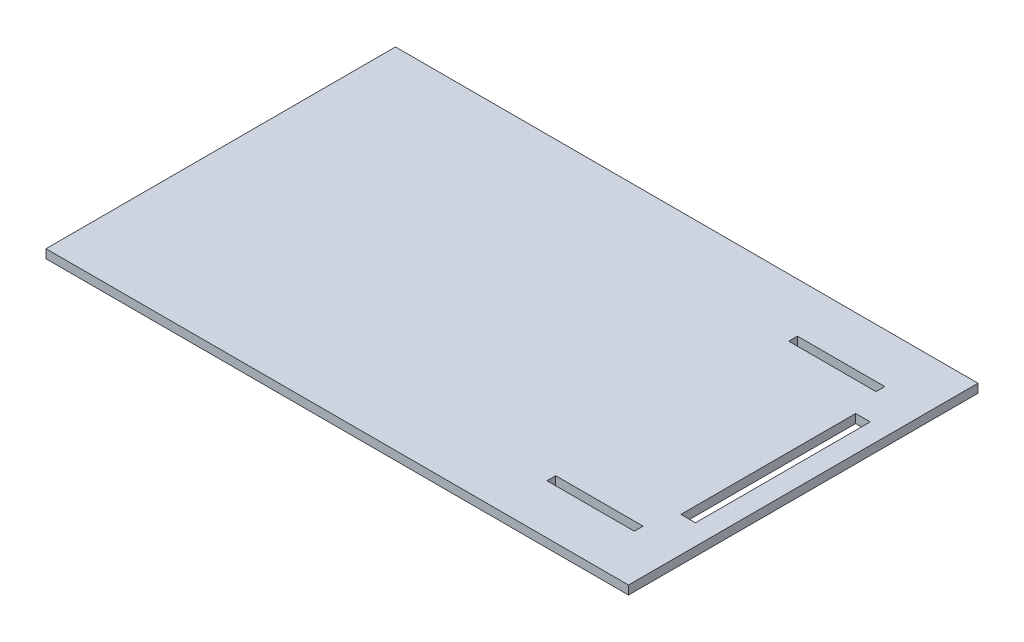
SolidWorks part; units mm, degrees
ref_plane "Front Plane" through (0, 0, 0) normal (0, 0, 1) x (1, 0, 0)
ref_plane "Top Plane" through (0, 0, 0) normal (0, 1, 0) x (1, 0, 0)
ref_plane "Right Plane" through (0, 0, 0) normal (1, 0, 0) x (0, 0, -1)
sketch "Sketch1" plane through (0, 0, 0) normal (0, 1, 0) x (1, 0, 0)
  line L1 (100, -60) -> (-100, -60)
  line L2 (100, -60) -> (100, 60)
  line L3 (100, 60) -> (-100, 60)
  line L4 (-100, -60) -> (-100, 60)
  line L5 (100, -60) -> (-100, 60) construction
  line L6 (100, 60) -> (-100, -60) construction
  point P0 (0, 0)
  dimension "D1" = 200
  dimension "D2" = 120
extrude "Boss-Extrude1" add sketch "Sketch1" along normal blind 3
sketch "Sketch2" plane through (0, 3, 0) normal (0, 1, 0) x (1, 0, 0)
  line L0 (0, 0) -> (100, 0) construction
  line L1 (88, 30) -> (93, 30)
  line L2 (88, 30) -> (88, -30)
  line L3 (88, -30) -> (93, -30)
  line L4 (93, 30) -> (93, -30)
  line L5 (88, 30) -> (93, -30) construction
  line L6 (88, -30) -> (93, 30) construction
  line L7 (100, -60) -> (100, 60) construction
  line L8 (100, 0) -> (0, 0) construction
  line L9 (0, 0) -> (0, 60) construction
  line L10 (100, 60) -> (-100, 60) construction
  line L11 (-100, -60) -> (100, -60) construction
  point P0 (90.5, 0)
  dimension "D1" = 60
  dimension "D2" = 5
  dimension "D3" = 7
  dimension "D4" = 30
extrude "Cut-Extrude1" cut sketch "Sketch2" against normal through all
sketch "Sketch3" plane through (0, 3, 0) normal (0, 1, 0) x (1, 0, 0)
  line L0 (100, -60) -> (100, 60) construction
  line L1 (55, 43) -> (85, 43)
  line L2 (55, 43) -> (55, 40)
  line L3 (55, 40) -> (85, 40)
  line L4 (85, 43) -> (85, 40)
  line L5 (55, 43) -> (85, 40) construction
  line L6 (55, 40) -> (85, 43) construction
  line L7 (0, 0) -> (100, 0) construction
  line L8 (85, -43) -> (85, -40)
  line L9 (55, -43) -> (85, -43)
  line L10 (55, -43) -> (55, -40)
  line L11 (55, -40) -> (85, -40)
  point P0 (70, 41.5)
  dimension "D1" = 3
  dimension "D2" = 30
  dimension "D3" = 15
  dimension "D4" = 40
extrude "Cut-Extrude2" cut sketch "Sketch3" against normal through all
